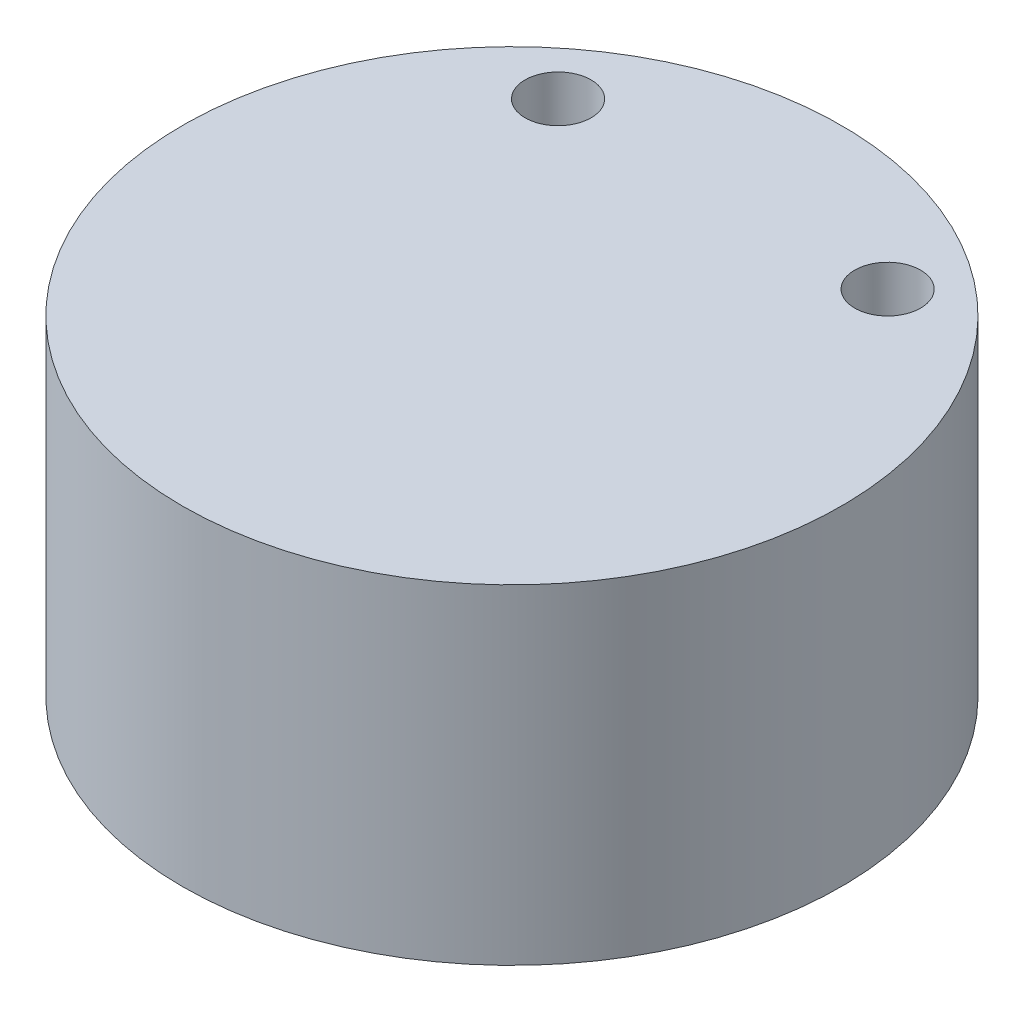
SolidWorks part; units mm, degrees
ref_plane "Front Plane" through (0, 0, 0) normal (0, 0, 1) x (1, 0, 0)
ref_plane "Top Plane" through (0, 0, 0) normal (0, 1, 0) x (1, 0, 0)
ref_plane "Right Plane" through (0, 0, 0) normal (1, 0, 0) x (0, 0, -1)
sketch "Sketch1" plane through (0, 0, 0) normal (0, 1, 0) x (1, 0, 0)
  circle A0 centre (0, 0) radius 3.9688
  dimension "D1" = 7.9375
extrude "Boss-Extrude1" add sketch "Sketch1" along normal blind 3.9688 contours A0
sketch "Sketch2" plane through (0, 0, 0) normal (0, -1, 0) x (1, 0, 0)
  line L0 (-3.0495, -2.54) -> (3.0495, -2.54) construction
  line L1 (0, 0) -> (0, -2.54) construction
  circle A1 centre (0, 0) radius 3.9688 construction
  circle A2 centre (-1.9844, -2.54) radius 0.3969
  circle A3 centre (1.9844, -2.54) radius 0.3969
  dimension "D2" = 0.7937
  dimension "D3" = 1.9844
  dimension "D1" = 2.54
extrude "Cut-Extrude1" cut sketch "Sketch2" against normal through all contours A3 | A2
